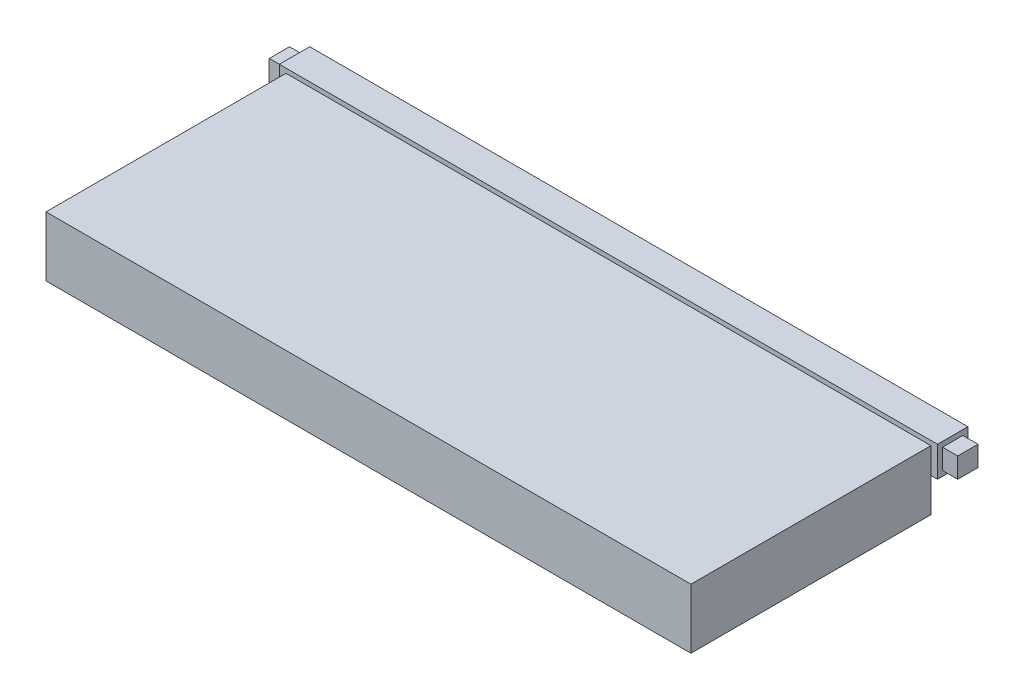
SolidWorks part; units mm, degrees
ref_plane "Front Plane" through (0, 0, 0) normal (0, 0, 1) x (1, 0, 0)
ref_plane "Top Plane" through (0, 0, 0) normal (0, 1, 0) x (1, 0, 0)
ref_plane "Right Plane" through (0, 0, 0) normal (1, 0, 0) x (0, 0, -1)
sketch "Sketch1" plane through (0, 0, 0) normal (0, 1, 0) x (1, 0, 0)
  line L1 (-335.2018, -5.5886) -> (314.7982, -5.5886)
  line L2 (-335.2018, -5.5886) -> (-335.2018, 24.4114)
  line L3 (-335.2018, 24.4114) -> (314.7982, 24.4114)
  line L4 (314.7982, -5.5886) -> (314.7982, 24.4114)
  line L5 (-335.2018, -5.5886) -> (314.7982, 24.4114) construction
  line L6 (-335.2018, 24.4114) -> (314.7982, -5.5886) construction
  point P0 (-10.2018, 9.4114)
  dimension "D1" = 650
  dimension "D2" = 30
extrude "Boss-Extrude1" add sketch "Sketch1" along normal blind 30
sketch "Sketch2" plane through (314.7982, 0, 0) normal (1, 0, 0) x (0, 0, -1)
  line L0 (-5.5886, 30) -> (-5.5886, 0) construction
  line L1 (-0.5886, 25) -> (19.4114, 25)
  line L2 (-0.5886, 25) -> (-0.5886, 5)
  line L3 (-0.5886, 5) -> (19.4114, 5)
  line L4 (19.4114, 25) -> (19.4114, 5)
  line L5 (-0.5886, 25) -> (19.4114, 5) construction
  line L6 (-0.5886, 5) -> (19.4114, 25) construction
  line L7 (-5.5886, 0) -> (24.4114, 0) construction
  point P0 (9.4114, 15)
  point P5 (0, 0)
  point P6 (9.4114, 15)
  point P7 (0, 0)
  point P8 (0, 0)
  point P9 (0, 0)
  point P10 (9.9375, 15.6248)
  dimension "D1" = 20
  dimension "D2" = 20
  dimension "D3" = 15
  dimension "D4" = 15
extrude "Boss-Extrude2" add sketch "Sketch2" along normal blind 15
sketch "Sketch3" plane through (-335.2018, 0, 0) normal (-1, 0, 0) x (0, 0, 1)
  line L1 (-19.4114, 5) -> (0.5886, 5)
  line L2 (-19.4114, 5) -> (-19.4114, 25)
  line L3 (-19.4114, 25) -> (0.5886, 25)
  line L4 (0.5886, 5) -> (0.5886, 25)
  line L5 (-19.4114, 5) -> (0.5886, 25) construction
  line L6 (-19.4114, 25) -> (0.5886, 5) construction
  line L7 (5.5886, 30) -> (5.5886, 0) construction
  line L8 (-24.4114, 30) -> (5.5886, 30) construction
  point P0 (-9.4114, 15)
  dimension "D1" = 20
  dimension "D2" = 20
  dimension "D3" = 15
  dimension "D4" = 15
extrude "Boss-Extrude3" add sketch "Sketch3" along normal blind 15
sketch "Sketch4" plane through (0, 0, 5.5886) normal (0, 0, 1) x (1, 0, 0)
  line L0 (-335.2018, 15) -> (314.7982, 15) construction
  line L1 (-335.2018, 5) -> (-335.2018, 25) construction
  line L2 (314.7982, 30) -> (314.7982, 0) construction
  line L3 (-10.2018, 30) -> (-10.2018, 0) construction
  line L4 (-335.2018, 30) -> (314.7982, 30) construction
  line L5 (-335.2018, 0) -> (314.7982, 0) construction
  line L7 (-328.6686, 25.5396) -> (308.265, 25.5396)
  line L8 (-328.6686, 25.5396) -> (-328.6686, 4.4604)
  line L9 (-328.6686, 4.4604) -> (308.265, 4.4604)
  line L10 (308.265, 25.5396) -> (308.265, 4.4604)
  line L11 (-328.6686, 25.5396) -> (308.265, 4.4604) construction
  line L12 (-328.6686, 4.4604) -> (308.265, 25.5396) construction
  point P12 (-10.2018, 15)
extrude "Boss-Extrude4" add sketch "Sketch4" along normal blind 237
sketch "Sketch6" plane through (0, 4.4604, 0) normal (0, -1, 0) x (1, 0, 0)
  line L4 (-328.6686, 5.5886) -> (308.265, 5.5886)
  line L5 (308.265, 5.5886) -> (308.265, 242.5886)
  line L6 (308.265, 242.5886) -> (-328.6686, 242.5886)
  line L7 (-328.6686, 242.5886) -> (-328.6686, 5.5886)
  line L8 (-328.6686, 5.5886) -> (308.265, 5.5886)
  line L9 (308.265, 5.5886) -> (308.265, 242.5886)
  line L10 (308.265, 242.5886) -> (-328.6686, 242.5886)
  line L11 (-328.6686, 242.5886) -> (-328.6686, 5.5886)
  line L16 (-318.6686, 15.5886) -> (298.265, 15.5886)
  line L17 (298.265, 15.5886) -> (298.265, 232.5886)
  line L18 (298.265, 232.5886) -> (-318.6686, 232.5886)
  line L19 (-318.6686, 232.5886) -> (-318.6686, 15.5886)
  line L20 (-318.6686, 15.5886) -> (298.265, 15.5886)
  line L21 (298.265, 15.5886) -> (298.265, 232.5886)
  line L22 (298.265, 232.5886) -> (-318.6686, 232.5886)
  line L23 (-318.6686, 232.5886) -> (-318.6686, 15.5886)
  dimension "D1" = 0
  dimension "D2" = 10
extrude "Boss-Extrude5" add sketch "Sketch6" along normal blind 38
